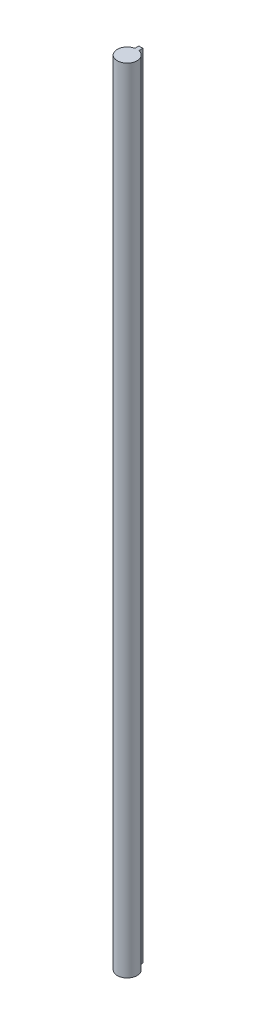
SolidWorks part; units mm, degrees
ref_plane "前视基准面" through (0, 0, 0) normal (0, 0, 1) x (1, 0, 0)
ref_plane "上视基准面" through (0, 0, 0) normal (0, 1, 0) x (1, 0, 0)
ref_plane "右视基准面" through (0, 0, 0) normal (1, 0, 0) x (0, 0, -1)
sketch "草图1" plane through (0, 0, 0) normal (0, 1, 0) x (1, 0, 0)
  line L1 (0, -6.6512) -> (0, 18.474) construction
  line L2 (-2, 9.798) -> (-2, 13.798)
  line L3 (-2, 13.798) -> (2, 13.798)
  line L4 (2, 9.798) -> (2, 13.798)
  arc A0 (-2, 9.798) -> (2, 9.798) centre (0, 0) ccw
  point P10 (0, 13.798)
  dimension "D1" = 4
  dimension "D3" = 10
  dimension "D2" = 4
extrude "凸台-拉伸1" add sketch "草图1" along normal blind 800
